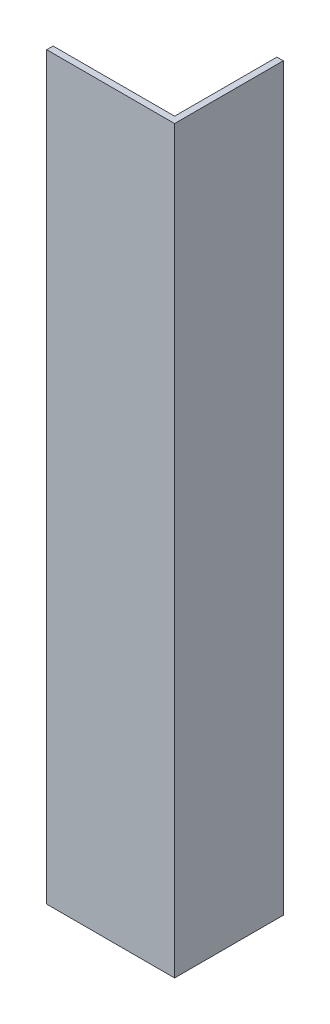
SolidWorks part; units mm, degrees
material "Acrylic (Medium-high impact)"
ref_plane "Front Plane" through (0, 0, 0) normal (0, 0, 1) x (1, 0, 0)
ref_plane "Top Plane" through (0, 0, 0) normal (0, 1, 0) x (1, 0, 0)
ref_plane "Right Plane" through (0, 0, 0) normal (1, 0, 0) x (0, 0, -1)
sketch "Sketch1" plane through (0, 0, 0) normal (0, 0, 1) x (1, 0, 0)
  line L0 (812.8, 457.2) -> (-406.4, 457.2) construction
  line L1 (812.8, 457.2) -> (-406.4, 457.2) construction
  line L2 (812.8, -277.5418) -> (-406.4, -277.5418) construction
  line L3 (812.8, -277.5418) -> (-406.4, -277.5418) construction
  line L5 (197.2469, 457.2) -> (190.8969, 457.2)
  line L6 (197.2469, 457.2) -> (197.2469, -277.5418)
  line L7 (197.2469, -277.5418) -> (190.8969, -277.5418)
  line L8 (190.8969, 457.2) -> (190.8969, -277.5418)
  line L9 (197.2469, 125.5526) -> (197.2469, -277.5418) construction
  line L10 (197.2469, 125.5526) -> (197.2469, -277.5418) construction
  dimension "D1" = 6.35
extrude "Boss-Extrude1" add sketch "Sketch1" along normal blind 107.95
sketch "Sketch2" plane through (190.8969, 0, 0) normal (-1, 0, 0) x (0, 0, 1)
  line L0 (107.95, -277.5418) -> (0, -277.5418) construction
  line L1 (107.95, 457.2) -> (101.6, 457.2)
  line L2 (107.95, 457.2) -> (107.95, -277.5418)
  line L3 (107.95, -277.5418) -> (101.6, -277.5418)
  line L4 (101.6, 457.2) -> (101.6, -277.5418)
  dimension "D1" = 6.35
extrude "Boss-Extrude2" add sketch "Sketch2" along normal blind 120.65
